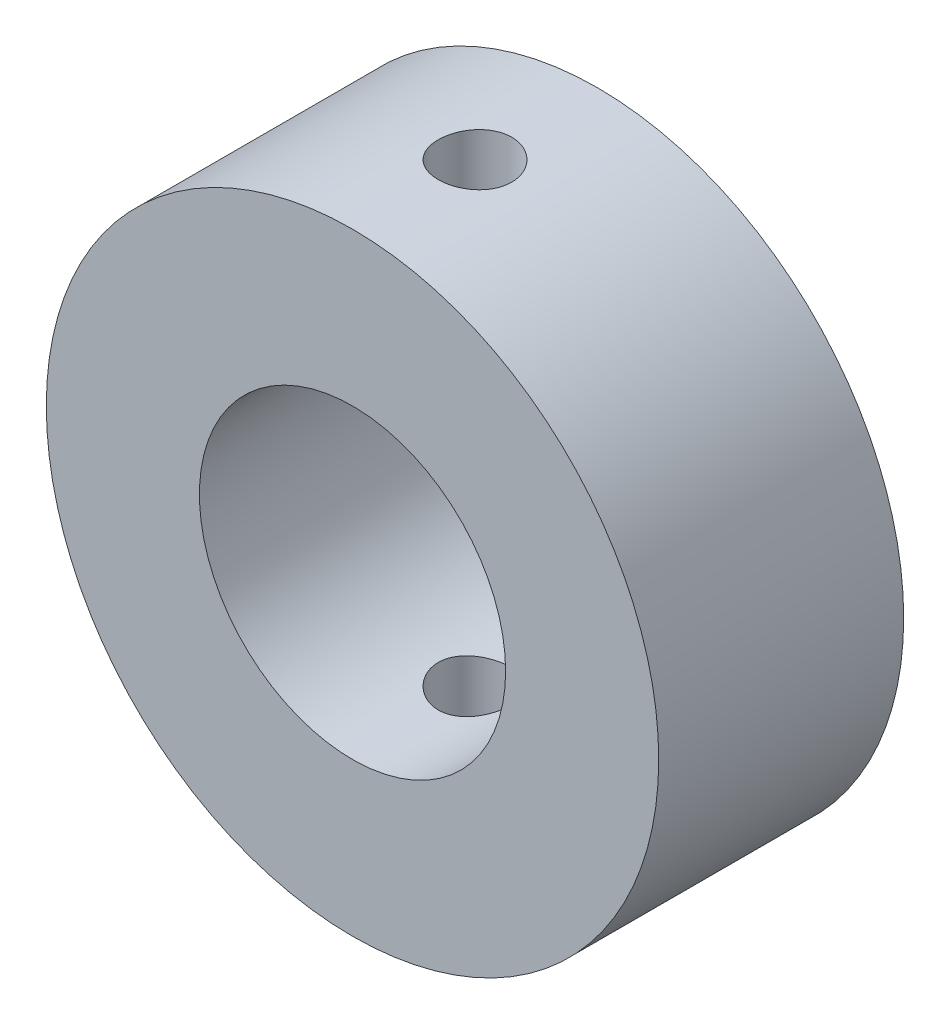
SolidWorks part; units mm, degrees
ref_plane "Front Plane" through (0, 0, 0) normal (0, 0, 1) x (1, 0, 0)
ref_plane "Top Plane" through (0, 0, 0) normal (0, 1, 0) x (1, 0, 0)
ref_plane "Right Plane" through (0, 0, 0) normal (1, 0, 0) x (0, 0, -1)
sketch "Sketch1" plane through (0, 0, 0) normal (0, 0, 1) x (1, 0, 0)
  circle A0 centre (0, 0) radius 25
  circle A1 centre (0, 0) radius 12.5
  dimension "D1" = 25
  dimension "D2" = 50
extrude "Boss-Extrude1" add sketch "Sketch1" along normal blind 20
sketch "Sketch2" plane through (0, 0, 0) normal (0, 1, 0) x (1, 0, 0)
  line L2 (25, 0) -> (-25, 0) construction
  circle A0 centre (0, -10) radius 3
  dimension "D1" = 6
  dimension "D2" = 10
extrude "Cut-Extrude1" cut sketch "Sketch2" against normal through all both and the other way through all
